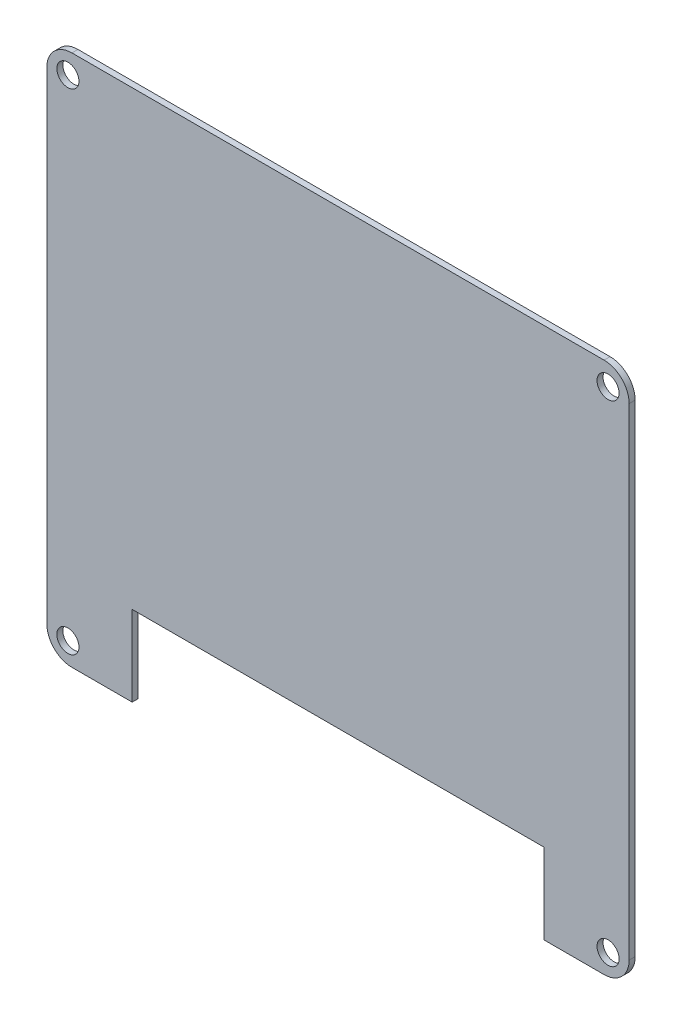
SolidWorks part; units mm, degrees
ref_plane "前视基准面" through (0, 0, 0) normal (0, 0, 1) x (1, 0, 0)
ref_plane "上视基准面" through (0, 0, 0) normal (0, 1, 0) x (1, 0, 0)
ref_plane "右视基准面" through (0, 0, 0) normal (1, 0, 0) x (0, 0, -1)
sketch "草图1" plane through (0, 0, 0) normal (0, 0, 1) x (1, 0, 0)
  line L0 (-1000, 0) -> (49000, 0) construction
  line L1 (-26.5, -26.5) -> (-20.5, -26.5)
  line L2 (-29, -24) -> (-29, 24)
  line L3 (-26.5, 26.5) -> (26.5, 26.5)
  line L4 (29, -24) -> (29, 24)
  line L5 (-29, -26.5) -> (29, 26.5) construction
  line L6 (-29, 26.5) -> (29, -26.5) construction
  line L7 (0, -1000) -> (0, 49000) construction
  line L8 (-20.5, -26.5) -> (-20.5, -18.5)
  line L9 (-20.5, -18.5) -> (20.5, -18.5)
  line L10 (20.5, -18.5) -> (20.5, -26.5)
  line L11 (20.5, -26.5) -> (26.5, -26.5)
  arc A0 (-26.5, -26.5) -> (-29, -24) centre (-26.5, -24) cw
  arc A1 (26.5, -26.5) -> (29, -24) centre (26.5, -24) ccw
  arc A2 (26.5, 26.5) -> (29, 24) centre (26.5, 24) cw
  arc A3 (-29, 24) -> (-26.5, 26.5) centre (-26.5, 24) cw
  circle A4 centre (-26.9, 24.4) radius 1.1
  circle A5 centre (-26.9, -24.4) radius 1.1
  circle A6 centre (26.9, -24.4) radius 1.1
  circle A7 centre (26.9, 24.4) radius 1.1
  point P0 (0, 0)
  dimension "D3" = 2.5
  dimension "D4" = 2.2
  dimension "D1" = 58
  dimension "D2" = 53
  dimension "D5" = 2.1
  dimension "D6" = 2.1
  dimension "D7" = 20.5
  dimension "D8" = 8
extrude "凸台-拉伸1" add sketch "草图1" along normal blind 0.6
